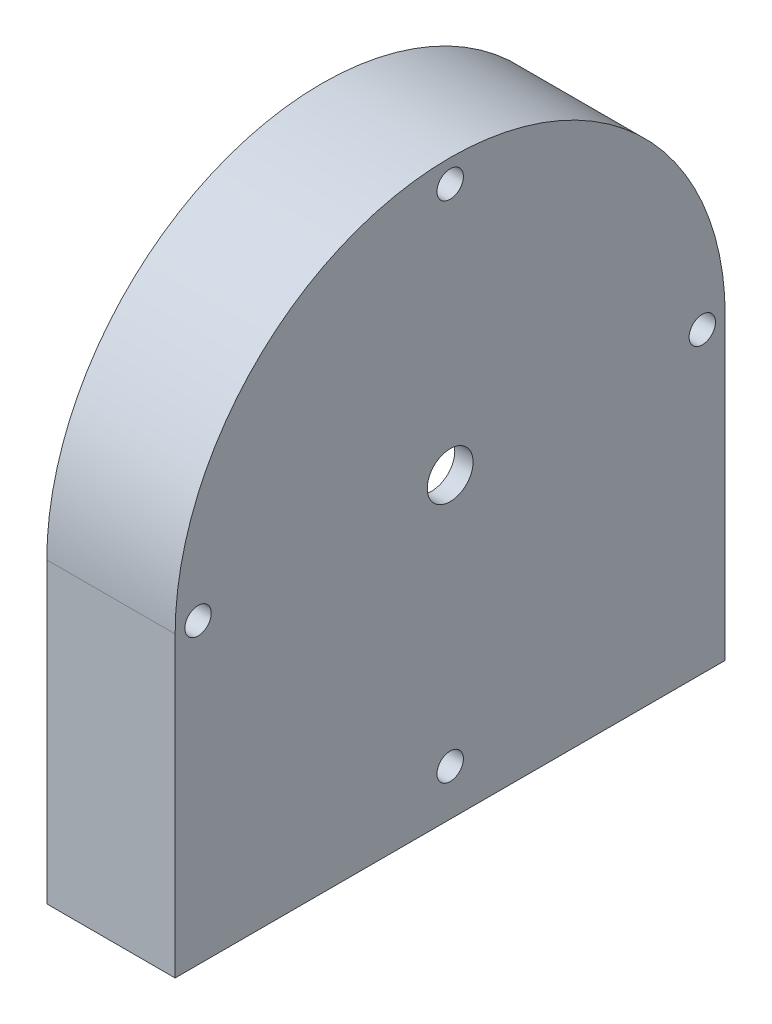
SolidWorks part; units mm, degrees
material "PE High Density"
ref_plane "Front Plane" through (0, 0, 0) normal (0, 0, 1) x (1, 0, 0)
ref_plane "Top Plane" through (0, 0, 0) normal (0, 1, 0) x (1, 0, 0)
ref_plane "Right Plane" through (0, 0, 0) normal (1, 0, 0) x (0, 0, -1)
sketch "Sketch1" plane through (0, 0, 0) normal (1, 0, 0) x (0, 0, -1)
  line L0 (-38.1, 0) -> (-38.1, -41.275)
  line L1 (-38.1, -41.275) -> (38.1, -41.275)
  line L2 (38.1, -41.275) -> (38.1, 0)
  circle A0 centre (0, 0) radius 38.1
  dimension "D1" = 76.2
  dimension "D2" = 3.175
extrude "Boss-Extrude1" add sketch "Sketch1" along normal blind 17.78 contours A0 L0 L1 L2 | A0
sketch "Sketch2" plane through (0, 0, 0) normal (-1, 0, 0) x (0, 0, 1)
  circle A0 centre (0, 0) radius 25.4
  dimension "D1" = 50.8
extrude "Cut-Extrude1" cut sketch "Sketch2" against normal blind 8.89
hole_wizard "#6 Clearance Hole1" positions "Sketch5" profile "Sketch4" hole size "#6" standard "ANSI Inch" end condition through all
sketch "Sketch5" plane through (17.78, 0, 0) normal (1, 0, 0) x (0, 0, -1)
  line L0 (0, 31.75) -> (0, 38.1) construction
  line L3 (31.75, 0) -> (38.1, 0) construction
  line L6 (0, -31.75) -> (0, -38.1) construction
  line L9 (-31.75, 0) -> (-38.1, 0) construction
  circle A1 centre (0, 0) radius 31.75
  arc A2 (38.1, 0) -> (-38.1, 0) centre (0, 0) ccw construction
  circle A3 centre (0, 0) radius 38.1
  point P36 (0, 34.925)
  point P38 (34.925, 0)
  point P40 (0, -34.925)
  point P42 (-34.925, 0)
  dimension "D1" = 6.35
sketch "Sketch4" plane through (17.78, 34.925, 0) normal (0, 1, 0) x (0, 0, -1)
  line L0 (0, 0) -> (0, 17.78)
  line L1 (0, 17.78) -> (1.8288, 17.78)
  line L2 (1.8288, 17.78) -> (1.8288, 0)
  line L5 (1.8288, 0) -> (0, 0)
  line L11 (0, -6.35) -> (0, 107.95) construction
  dimension "Thru Hole Dia." = 3.6576
  dimension "Thru Hole Depth" = 17.78
sketch "Sketch6" plane through (8.89, 0, 0) normal (-1, 0, 0) x (0, 0, 1)
  circle A0 centre (0, 0) radius 14.2875
  dimension "D1" = 28.575
extrude "Cut-Extrude2" cut sketch "Sketch6" against normal blind 6.35
sketch "Sketch7" plane through (17.78, 0, 0) normal (1, 0, 0) x (0, 0, -1)
  circle A0 centre (0, 0) radius 3.175
  dimension "D1" = 6.35
extrude "Cut-Extrude3" cut sketch "Sketch7" against normal through all
hole_wizard "#6 Clearance Hole2" positions "Sketch9" profile "Sketch8" hole size "#6" standard "ANSI Inch"
sketch "Sketch9" plane through (0, -41.275, 0) normal (0, -1, 0) x (-1, 0, 0)
  line L0 (-8.89, 38.1) -> (-8.89, -38.1) construction
  line L1 (-17.78, 38.1) -> (0, 38.1) construction
  line L2 (-17.78, -38.1) -> (0, -38.1) construction
  point P11 (-8.89, 25.4)
  point P13 (-8.89, -25.4)
  dimension "D1" = 12.7
  dimension "D2" = 12.7
sketch "Sketch8" plane through (8.89, -41.275, -25.4) normal (1, 0, 0) x (0, 0, -1)
  line L0 (0, 0) -> (0, 13.7989)
  line L1 (0, 13.7989) -> (1.8288, 12.7)
  line L2 (1.8288, 12.7) -> (1.8288, 0)
  line L5 (1.8288, 0) -> (0, 0)
  line L10 (0, 13.7989) -> (-1.8288, 12.7) construction
  line L11 (0, -6.35) -> (0, 107.95) construction
  dimension "Hole Dia." = 3.6576
  dimension "Hole Depth" = 12.7
  dimension "Drill Angle" = 118
